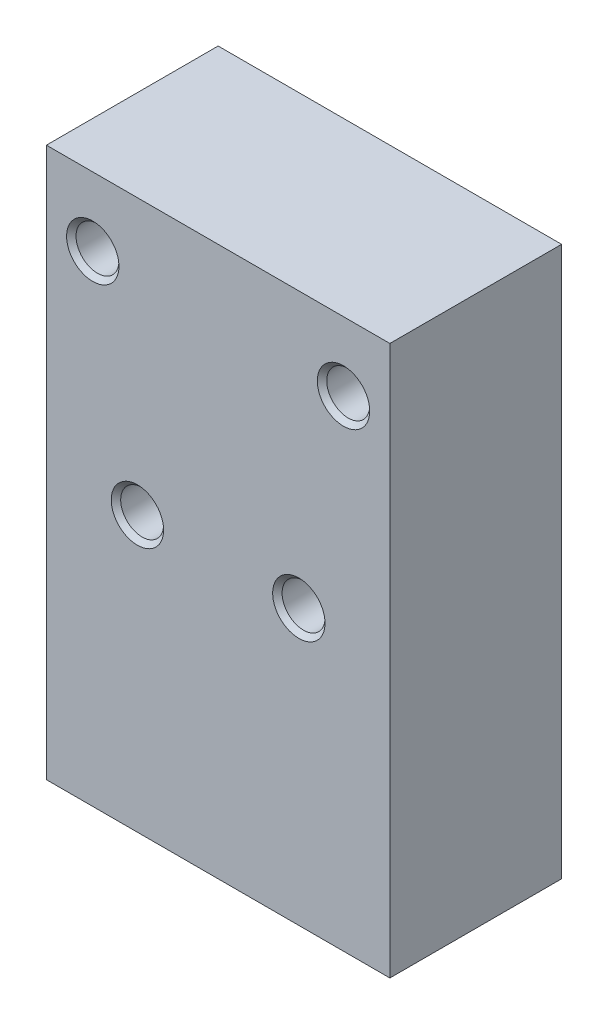
SolidWorks part; units mm, degrees
ref_plane "Front" through (0, 0, 0) normal (0, 0, 1) x (1, 0, 0)
ref_plane "Top" through (0, 0, 0) normal (0, 1, 0) x (1, 0, 0)
ref_plane "Right" through (0, 0, 0) normal (1, 0, 0) x (0, 0, -1)
sketch "草图1" plane through (0, 0, 0) normal (1, 0, 0) x (0, 0, -1)
  line L1 (0, 28) -> (-2, 28)
  line L2 (-2, 28) -> (-2, -2)
  line L3 (-2, -2) -> (8, -2)
  line L4 (8, -2) -> (8, 0)
  line L6 (0, 28) -> (8, 28)
  line L7 (8, 28) -> (8, 0)
  dimension "D3" = 30
  dimension "D4" = 10
extrude "凸台-拉伸1" add sketch "草图1" along normal blind 20
sketch "草图2" plane through (0, -2, 0) normal (0, -1, 0) x (1, 0, 0)
  line L0 (0, -3) -> (20, -3)
  line L1 (0, 2) -> (0, -8) construction
  line L2 (10, -3) -> (10, -3.7404)
  point P6 (5, -3)
  point P7 (15, -3)
  dimension "D1" = 10
  dimension "D2" = 5
hole_wizard "M3 螺纹孔1" positions "3D草图2" profile "草图4" tap size "M3" standard "ISO"
sketch3d "3D草图2"
  point P0 (5, -2, -3)
  point P3 (15, -2, -3)
cosmetic thread "孔螺蚊线1" parameters "D1"=6, "D2"=3
cosmetic thread "孔螺蚊线2" parameters "D1"=6, "D2"=3
sketch "草图4" plane through (5, -2, -3) normal (1, 0, 0) x (0, 0, -1)
  line L0 (0, 0) -> (0, 10.7511)
  line L1 (0, 10.7511) -> (1.25, 10)
  line L2 (1.25, 10) -> (1.25, 0.275)
  line L3 (1.25, 0.275) -> (1.525, 0)
  line L5 (1.525, 0) -> (0, 0)
  line L6 (-1.25, 0.275) -> (-1.525, 0) construction
  line L10 (0, 10.7511) -> (-1.25, 10) construction
  line L11 (0, -6.35) -> (0, 107.95) construction
  dimension "螺纹孔钻头直径" = 2.5
  dimension "螺纹孔钻头深度" = 10
  dimension "近端锥形沉头孔直径" = 3.05
  dimension "近端锥形沉头孔角度" = 90
  dimension "导头角度" = 118
sketch "草图5" plane through (0, 0, 2) normal (0, 0, 1) x (1, 0, 0)
  line L0 (14.7, 14) -> (14.7, 26)
  line L1 (14.7, 26) -> (2.7, 26)
  line L2 (2.7, 26) -> (14.7, 14)
  line L3 (20, 28) -> (20, -2) construction
  line L4 (20, 28) -> (0, 28) construction
  dimension "D1" = 12
  dimension "D2" = 12
  dimension "D3" = 5.3
  dimension "D4" = 2
hole_wizard "M3 螺纹孔2" positions "3D草图3" profile "草图6" tap size "M3" standard "ISO" end condition through all
sketch3d "3D草图3"
  point P0 (14.7, 14, 2)
  point P3 (2.7, 26, 2)
cosmetic thread "孔螺蚊线3" parameters "D2"=3
cosmetic thread "孔螺蚊线4" parameters "D2"=3
sketch "草图6" plane through (14.7, 14, 2) normal (1, 0, 0) x (0, -1, 0)
  line L0 (0, 0) -> (0, 10)
  line L1 (0, 10) -> (1.25, 10)
  line L2 (1.25, 10) -> (1.25, 0.275)
  line L3 (1.25, 0.275) -> (1.525, 0)
  line L5 (1.525, 0) -> (0, 0)
  line L6 (-1.25, 0.275) -> (-1.525, 0) construction
  line L11 (0, -6.35) -> (0, 107.95) construction
  dimension "通孔螺纹孔钻头直径" = 2.5
  dimension "通孔螺纹孔钻头深度" = 10
  dimension "近端锥形沉头孔直径" = 3.05
  dimension "近端锥形沉头孔角度" = 90
sketch "草图9" plane through (0, 0, 2) normal (0, 0, 1) x (1, 0, 0)
  line L0 (20, 28) -> (20, -2) construction
  line L1 (20, 27.7624) -> (0, 27.7624)
  line L2 (20, 27.7624) -> (20, 31)
  line L3 (20, 31) -> (0, 31)
  line L4 (0, 27.7624) -> (0, 31)
  line L5 (20, 28) -> (0, 28) construction
  dimension "D1" = 3
  dimension "D2" = 0.2376
sketch "草图10" plane through (0, 0, 2) normal (0, 0, 1) x (1, 0, 0)
  line L0 (10, 28) -> (10, 24.5383)
  line L1 (20, 28) -> (0, 28) construction
  point P0 (2.7, 26)
  point P1 (14.7, 14)
  point P8 (5.3, 14)
  point P9 (17.3, 26)
hole_wizard "M3 螺纹孔4" positions "3D草图5" profile "草图11" tap size "M3" standard "ISO" end condition through all
sketch3d "3D草图5"
  point P0 (5.3, 14, 2)
  point P3 (17.3, 26, 2)
cosmetic thread "孔螺蚊线7" parameters "D2"=3
cosmetic thread "孔螺蚊线8" parameters "D2"=3
sketch "草图11" plane through (5.3, 14, 2) normal (1, 0, 0) x (0, -1, 0)
  line L0 (0, 0) -> (0, 10)
  line L1 (0, 10) -> (1.25, 10)
  line L2 (1.25, 10) -> (1.25, 0.275)
  line L3 (1.25, 0.275) -> (1.525, 0)
  line L5 (1.525, 0) -> (0, 0)
  line L6 (-1.25, 0.275) -> (-1.525, 0) construction
  line L11 (0, -6.35) -> (0, 107.95) construction
  dimension "通孔螺纹孔钻头直径" = 2.5
  dimension "通孔螺纹孔钻头深度" = 10
  dimension "近端锥形沉头孔直径" = 3.05
  dimension "近端锥形沉头孔角度" = 90
extrude "凸台-拉伸2" add sketch "草图9" against normal blind 2
sketch "草图12" plane through (0, 0, 2) normal (0, 0, 1) x (1, 0, 0)
  line L0 (17.3, 26) -> (17.3, 30) construction
  line L1 (20, 30) -> (0, 30)
  line L2 (20, 30) -> (20, 41.0281)
  line L3 (0, 30) -> (0, 41.0281)
  line L4 (20, 41.0281) -> (0, 41.0281)
  line L5 (20, 31) -> (20, -2) construction
  line L6 (0, 31) -> (0, -2) construction
  dimension "D1" = 4
extrude "切除-拉伸1" cut sketch "草图12" against normal through all
sketch "草图13" plane through (0, 28, 0) normal (0, 1, 0) x (1, 0, 0)
  line L4 (0, 0) -> (20, 0)
  line L5 (20, 0) -> (20, 8)
  line L6 (20, 8) -> (0, 8)
  line L7 (0, 8) -> (0, 0)
  line L9 (20, 0) -> (20, 8)
  line L10 (20, 8) -> (0, 8)
  line L11 (0, 8) -> (0, 0)
  line L13 (0, 0) -> (20, 0)
  dimension "D1" = 0
extrude "凸台-拉伸3" add sketch "草图13" along normal up to surface (2 mm away) up to face at (10, 30, 1)
sketch "草图14" plane through (0, 30, 0) normal (0, 1, 0) x (1, 0, 0)
  line L0 (20, 8) -> (20, -2) construction
  line L1 (0, 8) -> (20, 8)
  line L2 (0, 8) -> (0, 1)
  line L3 (0, 1) -> (20, 1)
  line L4 (20, 8) -> (20, 1)
  line L5 (0, -2) -> (20, -2) construction
  dimension "D1" = 3
extrude "切除-拉伸2" [suppressed] cut sketch "草图14" against normal blind 27
